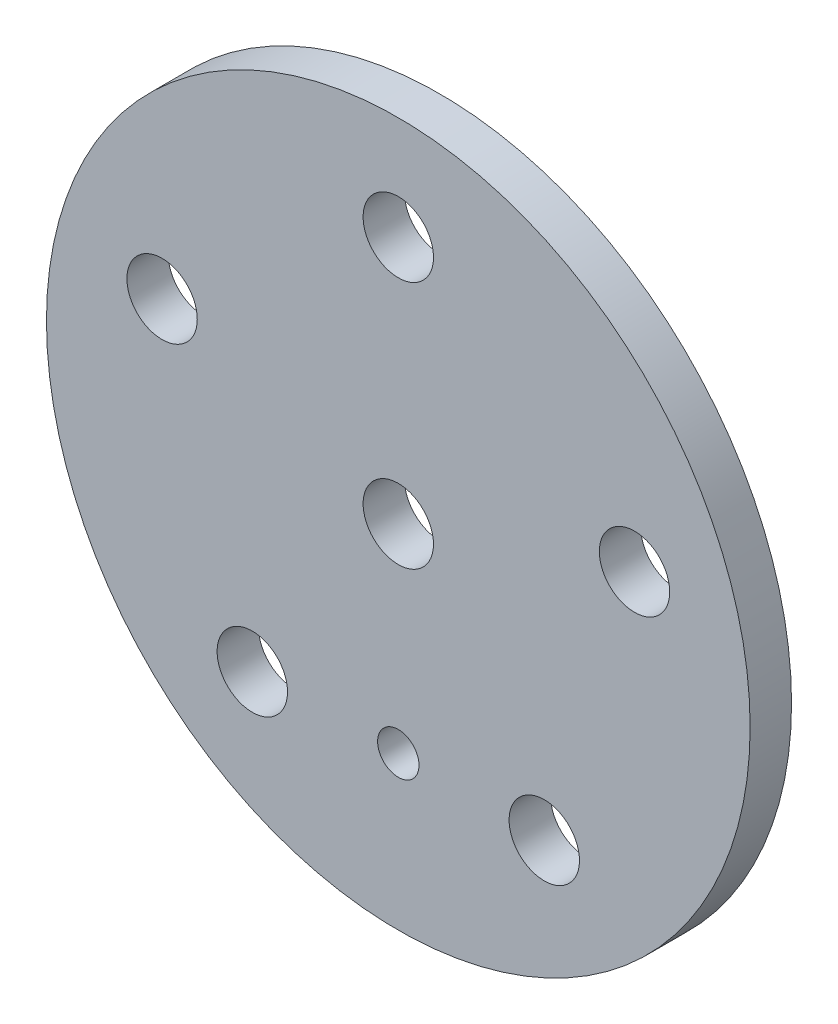
SolidWorks part; units mm, degrees
ref_plane "Front Plane" through (0, 0, 0) normal (0, 0, 1) x (1, 0, 0)
ref_plane "Top Plane" through (0, 0, 0) normal (0, 1, 0) x (1, 0, 0)
ref_plane "Right Plane" through (0, 0, 0) normal (1, 0, 0) x (0, 0, -1)
sketch "Sketch1" plane through (0, 0, 0) normal (0, 0, 1) x (1, 0, 0)
  circle A0 centre (0, 0) radius 85
  circle A1 centre (0, 0) radius 8.5
  dimension "D1" = 170
  dimension "D2" = 17
extrude "Boss-Extrude1" add sketch "Sketch1" along normal blind 10
sketch "Sketch2" plane through (0, 0, 10) normal (0, 0, 1) x (1, 0, 0)
  line L0 (0, 88.0267) -> (0, -92.7028) construction
  circle A0 centre (0, 60) radius 8.5
  circle A1 centre (57.0634, 18.541) radius 8.5
  circle A2 centre (35.2671, -48.541) radius 8.5
  circle A3 centre (-35.2671, -48.541) radius 8.5
  circle A4 centre (-57.0634, 18.541) radius 8.5
  point P16 (0, 0)
  dimension "D1" = 17
  dimension "D2" = 60
  dimension "D3" = 5
extrude "Cut-Extrude1" cut sketch "Sketch2" against normal blind 10
sketch "Sketch4" plane through (0, 0, 10) normal (0, 0, 1) x (1, 0, 0)
  circle A0 centre (0, -48) radius 5
  dimension "D1" = 10
  dimension "D2" = 48
extrude "Cut-Extrude3" cut sketch "Sketch4" against normal blind 60
